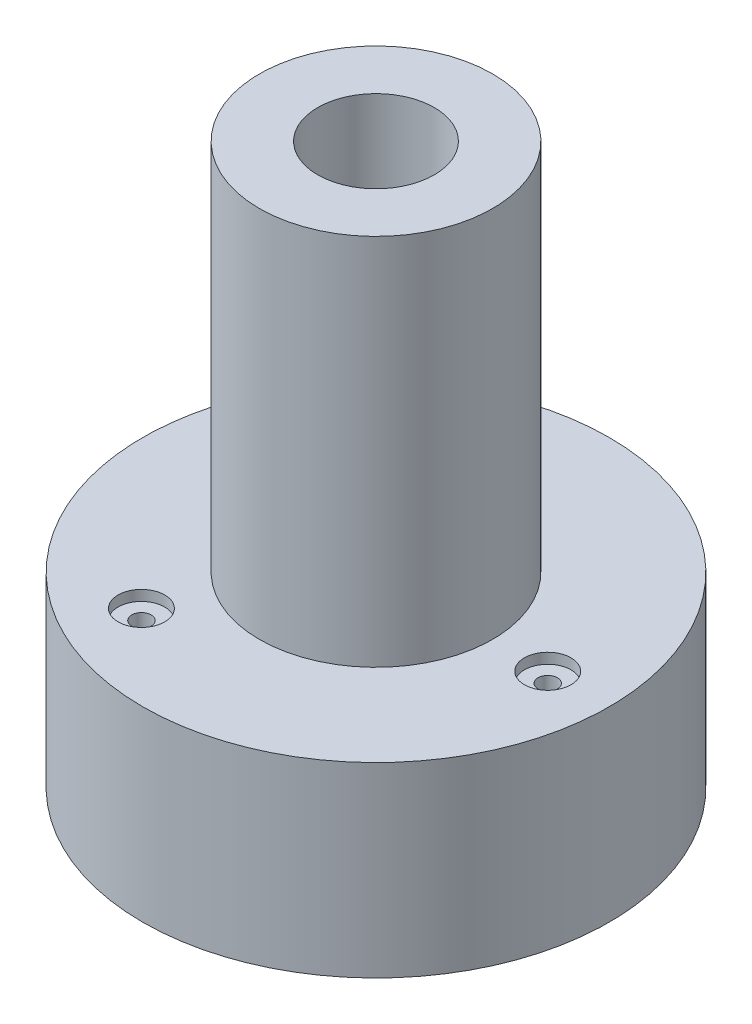
SolidWorks part; units mm, degrees
ref_plane "Front Plane" through (0, 0, 0) normal (0, 0, 1) x (1, 0, 0)
ref_plane "Top Plane" through (0, 0, 0) normal (0, 1, 0) x (1, 0, 0)
ref_plane "Right Plane" through (0, 0, 0) normal (1, 0, 0) x (0, 0, -1)
sketch "Sketch1" plane through (0, 0, 0) normal (0, 1, 0) x (1, 0, 0)
  circle A0 centre (0, 0) radius 7.9375
  dimension "D1" = 15.875
extrude "Boss-Extrude1" add sketch "Sketch1" along normal blind 25.4
sketch "Sketch2" plane through (0, 0, 0) normal (0, -1, 0) x (-1, 0, 0)
  circle A0 centre (0, 0) radius 15.875
  dimension "D1" = 31.75
extrude "Boss-Extrude2" add sketch "Sketch2" along normal blind 12.7
sketch "Sketch3" plane through (0, 25.4, 0) normal (0, 1, 0) x (1, 0, 0)
  circle A0 centre (0, 0) radius 3.9688
  dimension "D1" = 7.9375
extrude "Cut-Extrude1" cut sketch "Sketch3" against normal blind 19.05
hole_wizard "CBORE for #00 Binding Head Machine Screw1" positions "Sketch4" profile "Sketch5" counterbore size "#00" standard "ANSI Inch" end condition through all
sketch "Sketch4" plane through (0, 0, 0) normal (0, 1, 0) x (1, 0, 0)
  point P0 (11.6877, 0)
sketch "Sketch5" plane through (11.6877, 0, 0) normal (1, 0, 0) x (0, 0, 1)
  line L0 (0, 0) -> (0, 12.7)
  line L1 (0, 12.7) -> (0.6604, 12.7)
  line L3 (0.6604, 12.7) -> (0.6604, 0.7112)
  line L4 (0.6604, 0.7112) -> (1.5875, 0.7112)
  line L5 (1.5875, 0.7112) -> (1.5875, 0)
  line L7 (1.5875, 0) -> (0, 0)
  line L11 (0, -6.35) -> (0, 107.95) construction
  dimension "Thru Hole Dia." = 1.3208
  dimension "Thru Hole Depth" = 12.7
  dimension "C'Bore Dia." = 3.175
  dimension "C'Bore Depth" = 0.7112
pattern_circular "CirPattern1" count 3 every 120 about axis through (0, 0, 0) along (0, 1, 0) of "CBORE for #00 Binding Head Machine Screw1"
